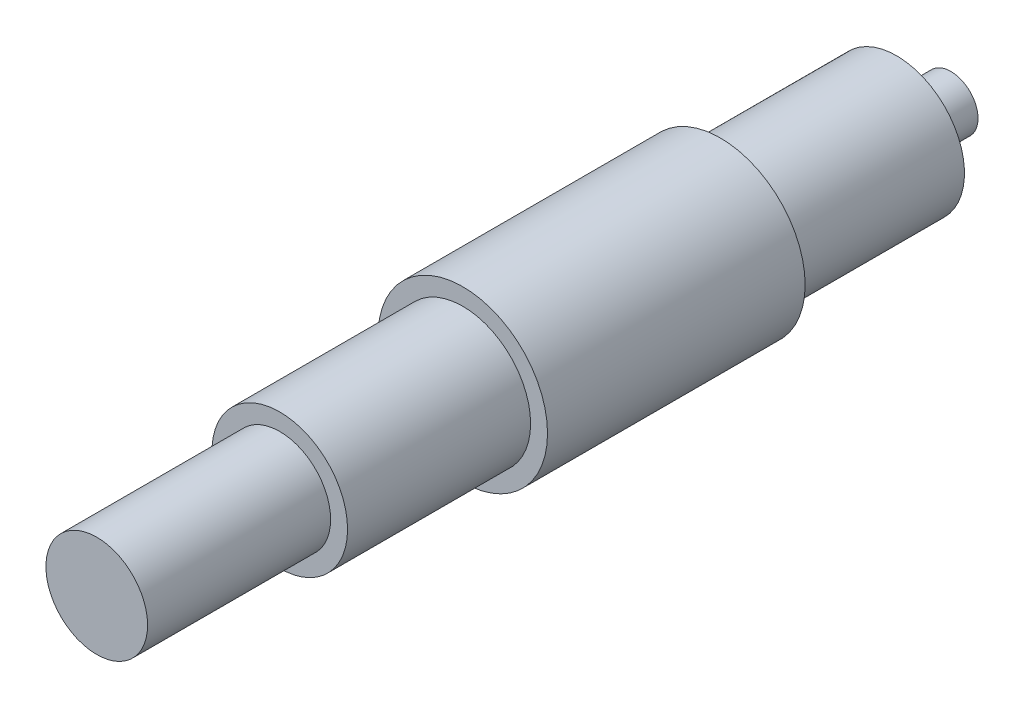
SolidWorks part; units mm, degrees
ref_plane "Plan de face" through (0, 0, 0) normal (0, 0, 1) x (1, 0, 0)
ref_plane "Plan de dessus" through (0, 0, 0) normal (0, 1, 0) x (1, 0, 0)
ref_plane "Plan de droite" through (0, 0, 0) normal (1, 0, 0) x (0, 0, -1)
sketch "Sketch1" plane through (0, 0, 0) normal (0, 0, 1) x (1, 0, 0)
  circle A0 centre (0, 0) radius 4
  dimension "D1" = 8
extrude "Boss-Extrude1" add sketch "Sketch1" along normal blind 8
sketch "Sketch2" plane through (0, 0, 8) normal (0, 0, 1) x (1, 0, 0)
  circle A0 centre (0, 0) radius 10
  dimension "D1" = 20
extrude "Boss-Extrude2" add sketch "Sketch2" along normal blind 26
sketch "Sketch3" plane through (0, 0, 34) normal (0, 0, 1) x (1, 0, 0)
  circle A0 centre (0, 0) radius 12.5
  dimension "D1" = 25
extrude "Boss-Extrude3" add sketch "Sketch3" along normal blind 38
sketch "Sketch4" plane through (0, 0, 72) normal (0, 0, 1) x (1, 0, 0)
  circle A0 centre (0, 0) radius 10
  dimension "D1" = 20
extrude "Boss-Extrude4" add sketch "Sketch4" along normal blind 20
sketch "Sketch5" plane through (0, 0, 92) normal (0, 0, 1) x (1, 0, 0)
  circle A0 centre (0, 0) radius 7.5
  dimension "D1" = 15
extrude "Boss-Extrude5" add sketch "Sketch5" along normal blind 34
ref_plane "Plane1" through (0, -7.5, 0) normal (0, -1, 0) x (-1, 0, 0)
sketch "Sketch7" plane through (0, -7.5, 0) normal (0, -1, 0) x (-1, 0, 0)
  line L0 (-7.5, -126) -> (7.5, -126) construction
  line L1 (-8.5, -111) -> (1.5, -111)
  line L2 (-8.5, -111) -> (-8.5, -126)
  line L3 (-8.5, -126) -> (1.5, -126)
  line L4 (1.5, -111) -> (1.5, -126)
  line L5 (-8.5, -111) -> (1.5, -126) construction
  line L6 (-8.5, -126) -> (1.5, -111) construction
  line L7 (-7.5, -92) -> (-7.5, -126) construction
  point P0 (-3.5, -118.5)
  dimension "D1" = 15
  dimension "D2" = 0
  dimension "D3" = 10
  dimension "D4" = 4
sketch "Sketch8" plane through (0, 0, 92) normal (0, 0, 1) x (1, 0, 0)
  circle A0 centre (0, 0) radius 10
  circle A1 centre (0, 0) radius 7.5
extrude "Boss-Extrude6" add sketch "Sketch8" along normal blind 7
